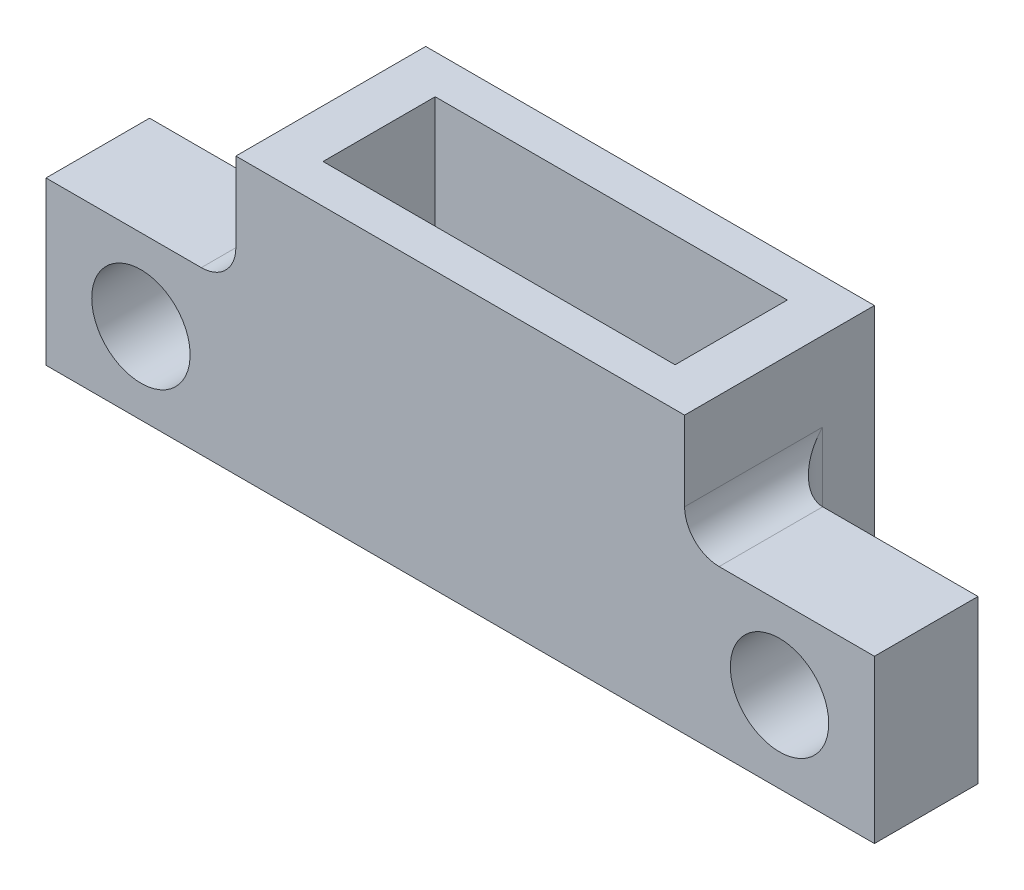
SolidWorks part; units mm, degrees
ref_plane "Front Plane" through (0, 0, 0) normal (0, 0, 1) x (1, 0, 0)
ref_plane "Top Plane" through (0, 0, 0) normal (0, 1, 0) x (1, 0, 0)
ref_plane "Right Plane" through (0, 0, 0) normal (1, 0, 0) x (0, 0, -1)
sketch "Sketch2" plane through (0, 0, 0) normal (0, 1, 0) x (1, 0, 0)
  line L0 (-13, 5.5) -> (13, -5.5) construction
  line L1 (-13, -5.5) -> (13, -5.5)
  line L2 (-13, -5.5) -> (-13, 5.5)
  line L3 (-13, 5.5) -> (13, 5.5)
  line L4 (13, -5.5) -> (13, 5.5)
  line L5 (-13, -5.5) -> (13, 5.5) construction
  line L6 (-10.2, 3.25) -> (10.2, -3.25) construction
  line L7 (-10.2, -3.25) -> (10.2, -3.25)
  line L8 (-10.2, -3.25) -> (-10.2, 3.25)
  line L9 (-10.2, 3.25) -> (10.2, 3.25)
  line L10 (10.2, -3.25) -> (10.2, 3.25)
  line L11 (10.2, 3.25) -> (-10.2, -3.25) construction
  point P1 (0, 0)
  point P6 (0, 0)
  point P11 (10.2, 0)
  dimension "D1" = 26
  dimension "D2" = 11
  dimension "D3" = 20.4
  dimension "D4" = 6.5
  dimension "D5" = 0
  dimension "D6" = 10.2
extrude "Boss-Extrude1" add sketch "Sketch2" along normal blind 10
sketch "Sketch3" plane through (0, 0, 0) normal (0, -1, 0) x (1, 0, 0)
  line L0 (-10.2, 3.25) -> (10.2, 3.25) construction
  line L1 (-13, 5.5) -> (13, 5.5)
  line L2 (-13, 5.5) -> (-13, -5.5)
  line L3 (-13, -5.5) -> (13, -5.5)
  line L4 (13, 5.5) -> (13, -5.5)
  line L5 (10.2, -3.25) -> (-10.2, -3.25) construction
  line L6 (-8.7, 3.25) -> (-6.2, 3.25)
  line L7 (-8.7, 3.25) -> (-8.7, -3.25)
  line L8 (-8.7, -3.25) -> (-6.2, -3.25)
  line L9 (-6.2, 3.25) -> (-6.2, -3.25)
  line L10 (-10.2, -3.25) -> (-10.2, 3.25) construction
  line L11 (-1.5, 3.25) -> (1, 3.25)
  line L12 (-1.5, 3.25) -> (-1.5, -3.25)
  line L13 (-1.5, -3.25) -> (1, -3.25)
  line L14 (1, 3.25) -> (1, -3.25)
  line L15 (6.2, 3.25) -> (8.7, 3.25)
  line L16 (6.2, 3.25) -> (6.2, -3.25)
  line L17 (6.2, -3.25) -> (8.7, -3.25)
  line L18 (8.7, 3.25) -> (8.7, -3.25)
  line L19 (10.2, 3.25) -> (10.2, -3.25) construction
  point P26 (-7.45, 3.25)
  point P27 (-0.25, 3.25)
  dimension "D1" = 2.5
  dimension "D2" = 2.5
  dimension "D3" = 2.5
  dimension "D4" = 1.5
  dimension "D5" = 1.5
  dimension "D6" = 7.2
extrude "Boss-Extrude2" add sketch "Sketch3" along normal blind 6
sketch "Sketch4" plane through (0, 0, 5.5) normal (0, 0, 1) x (1, 0, 0)
  line L0 (0, -6.05) -> (0, 6.05) construction
  line L1 (13, -6) -> (24, -6)
  line L2 (13, -6) -> (13, 3.4)
  line L3 (13, 3.4) -> (24, 3.4)
  line L4 (24, -6) -> (24, 3.4)
  line L5 (-13, -6) -> (-24, -6)
  line L6 (-13, -6) -> (-13, 3.4)
  line L7 (-13, 3.4) -> (-24, 3.4)
  line L8 (-24, -6) -> (-24, 3.4)
  circle A0 centre (18.5, -1.3) radius 2.85
  circle A1 centre (-18.5, -1.3) radius 2.85
  dimension "D5" = 5.7
  dimension "D1" = 9.4
  dimension "D2" = 11
  dimension "D3" = 4.7
  dimension "D4" = 5.5
extrude "Boss-Extrude3" add sketch "Sketch4" against normal blind 6
fillet "Fillet1" radius 2 4 edges at (-13, 3.4, 2.5) (-13, -1.3, -0.5) (13, 3.4, 2.5) (13, -1.3, -0.5)
